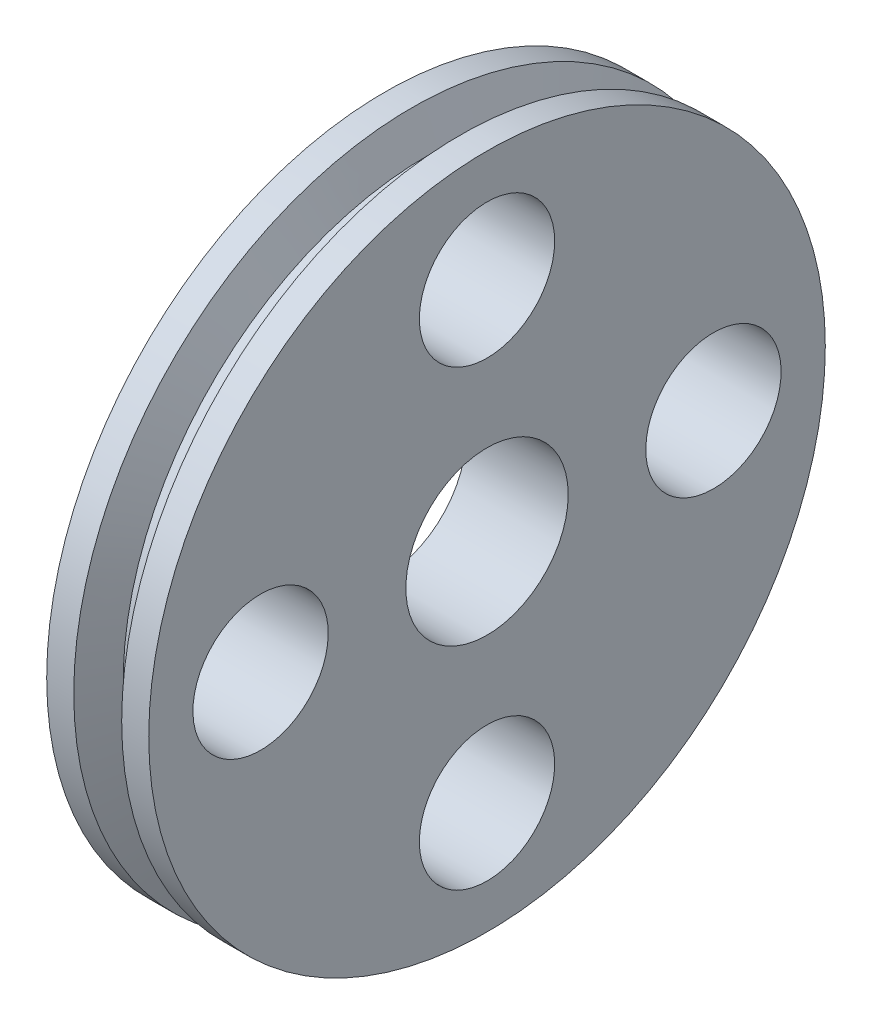
SolidWorks part; units mm, degrees
ref_plane "Front Plane" through (0, 0, 0) normal (0, 0, 1) x (1, 0, 0)
ref_plane "Top Plane" through (0, 0, 0) normal (0, 1, 0) x (1, 0, 0)
ref_plane "Right Plane" through (0, 0, 0) normal (1, 0, 0) x (0, 0, -1)
sketch "Sketch1" plane through (0, 0, 0) normal (0, 0, 1) x (1, 0, 0)
  line L0 (0, 0) -> (-102.6049, 0) construction
  line L1 (-20.8549, 24) -> (-51.0215, 24)
  line L2 (-51.0215, 24) -> (-51.0215, 100)
  line L3 (-51.0215, 100) -> (-43.0215, 100)
  line L4 (-43.0215, 100) -> (-38.4382, 90)
  line L5 (-38.4382, 90) -> (-33.4382, 90)
  line L6 (-33.4382, 90) -> (-28.8549, 100)
  line L7 (-28.8549, 100) -> (-20.8549, 100)
  line L8 (-20.8549, 100) -> (-20.8549, 24)
  dimension "D1" = 10
  dimension "D2" = 5
  dimension "D3" = 8
  dimension "D4" = 24
  dimension "D5" = 100
revolve "Revolve1" add sketch "Sketch1" angle 360 about L0
sketch "Sketch2" plane through (-20.8549, 0, 0) normal (1, 0, 0) x (0, 0, -1)
  circle A0 centre (0, 66.9369) radius 20
  dimension "D1" = 40
extrude "Cut-Extrude1" cut sketch "Sketch2" against normal blind 103
pattern_circular "CirPattern1" count 4 over 360 about axis through (0, 0, 0) along (1, 0, 0) of "Cut-Extrude1"
